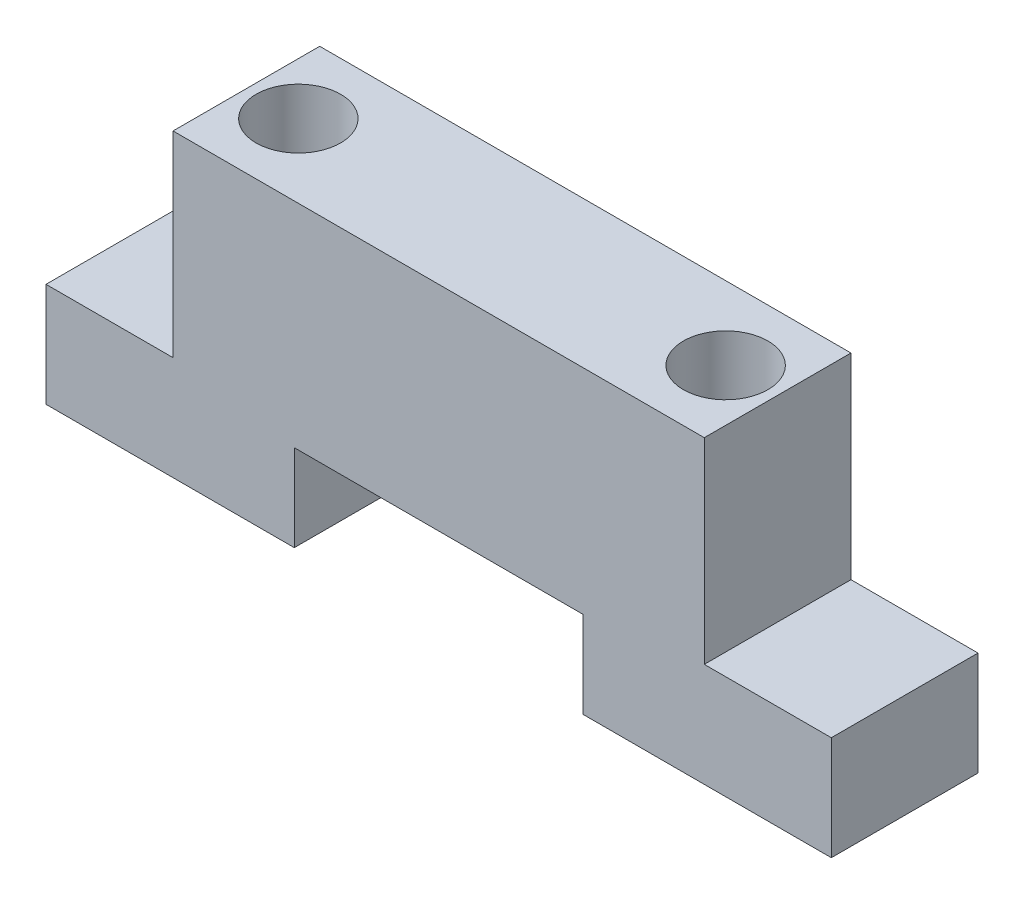
SolidWorks part; units mm, degrees
material "ABS"
ref_plane "Front Plane" through (0, 0, 0) normal (0, 0, 1) x (1, 0, 0)
ref_plane "Top Plane" through (0, 0, 0) normal (0, 1, 0) x (1, 0, 0)
ref_plane "Right Plane" through (0, 0, 0) normal (1, 0, 0) x (0, 0, -1)
sketch "Sketch1" plane through (0, 0, 0) normal (0, 0, 1) x (1, 0, 0)
  line L0 (0, 0) -> (0, 4.5)
  line L1 (0, 4.5) -> (5.5, 4.5)
  line L2 (5.5, 4.5) -> (5.5, 13)
  line L3 (5.5, 13) -> (28.5, 13)
  line L4 (28.5, 13) -> (28.5, 4.5)
  line L5 (28.5, 4.5) -> (34, 4.5)
  line L6 (34, 4.5) -> (34, 0)
  line L7 (10.75, 3.75) -> (23.25, 3.75)
  line L11 (23.25, 3.75) -> (23.25, 0)
  line L12 (34, 0) -> (23.25, 0)
  line L14 (10.75, 3.75) -> (10.75, 0)
  line L15 (10.75, 0) -> (0, 0)
  dimension "D1" = 4.5
  dimension "D2" = 3.75
  dimension "D3" = 10.75
  dimension "D4" = 5.5
  dimension "D5" = 12.5
  dimension "D6" = 10.75
  dimension "D7" = 13
  dimension "D8" = 5.5
  dimension "D9" = 4.5
extrude "Boss-Extrude1" add sketch "Sketch1" along normal blind 6.35
hole_wizard "#6 Clearance Hole1" positions "3DSketch1" profile "Sketch5" hole size "#6" standard "Ansi Inch" end condition through all
sketch3d "3DSketch1"
  line L2 (28.5, 13, 3.175) -> (5.5, 13, 3.175) construction
  line L3 (28.5, 13, 6.35) -> (28.5, 13, 0) construction
  line L4 (5.5, 13, 6.35) -> (5.5, 13, 0) construction
  line L6 (17, 13, 6.35) -> (17, 13, 0) construction
  line L7 (28.5, 13, 6.35) -> (5.5, 13, 6.35) construction
  line L8 (28.5, 13, 0) -> (5.5, 13, 0) construction
  point P0 (26.25, 13, 3.175)
  point P4 (7.75, 13, 3.175)
  dimension "D1" = 9.25
  dimension "D2" = 9.25
sketch "Sketch5" plane through (26.25, 13, 3.175) normal (1, 0, 0) x (0, 0, 1)
  line L0 (0, 0) -> (0, 13)
  line L1 (0, 13) -> (1.8288, 13)
  line L2 (1.8288, 13) -> (1.8288, 0)
  line L5 (1.8288, 0) -> (0, 0)
  line L11 (0, -6.35) -> (0, 107.95) construction
  dimension "Thru Hole Dia." = 3.6576
  dimension "Thru Hole Depth" = 13
